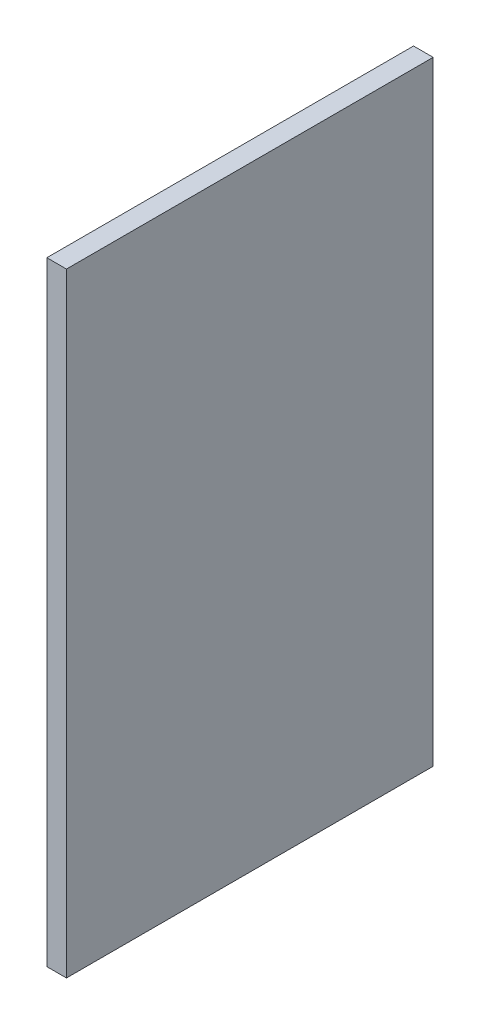
SolidWorks part; units mm, degrees
material "Pine"
ref_plane "Front Plane" through (0, 0, 0) normal (0, 0, 1) x (1, 0, 0)
ref_plane "Top Plane" through (0, 0, 0) normal (0, 1, 0) x (1, 0, 0)
ref_plane "Right Plane" through (0, 0, 0) normal (1, 0, 0) x (0, 0, -1)
sketch "Sketch1" plane through (0, 0, 0) normal (1, 0, 0) x (0, 0, -1)
  line L1 (0, 0) -> (-341.3125, 0)
  line L2 (0, 0) -> (0, 571.5)
  line L3 (0, 571.5) -> (-341.3125, 571.5)
  line L4 (-341.3125, 0) -> (-341.3125, 571.5)
  dimension "D1" = 341.3125
  dimension "D2" = 571.5
extrude "Boss-Extrude1" add sketch "Sketch1" along normal blind 18.2562
